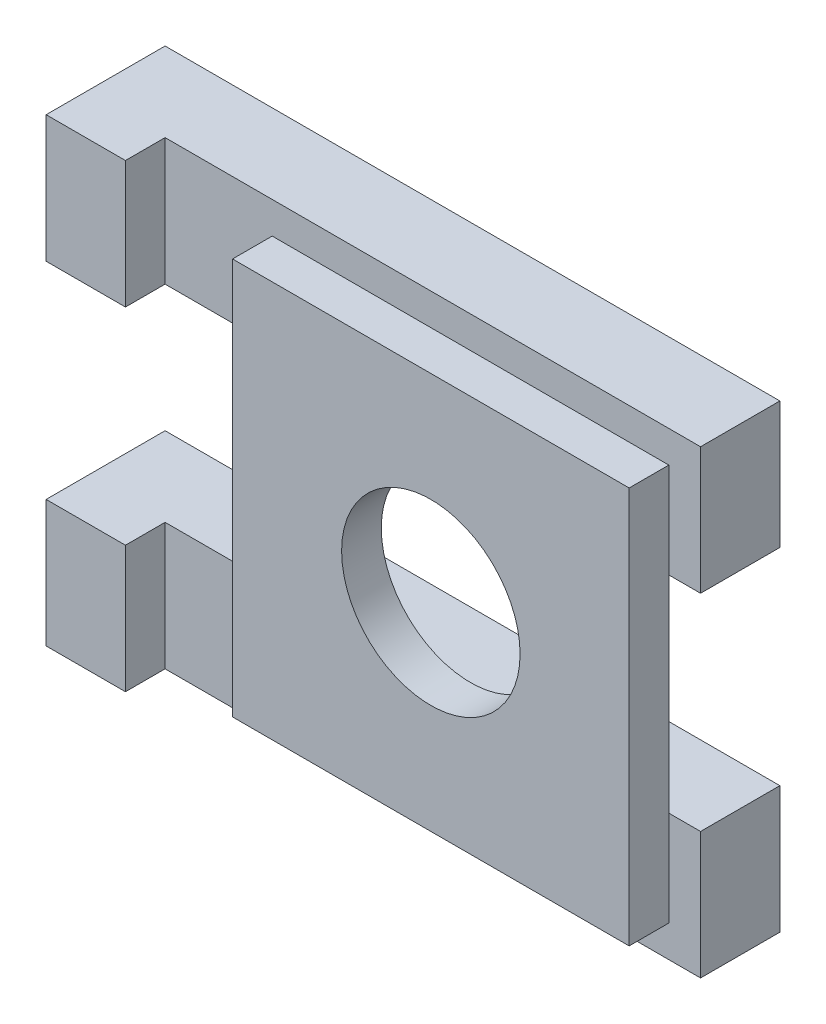
SolidWorks part; units mm, degrees
ref_plane "Płaszczyzna przednia" through (0, 0, 0) normal (0, 0, 1) x (1, 0, 0)
ref_plane "Płaszczyzna górna" through (0, 0, 0) normal (0, 1, 0) x (1, 0, 0)
ref_plane "Płaszczyzna prawa" through (0, 0, 0) normal (1, 0, 0) x (0, 0, -1)
sketch "Szkic1" plane through (0, 0, 0) normal (0, 0, 1) x (1, 0, 0)
  line L1 (-50, 50) -> (50, 50)
  line L2 (-50, 50) -> (-50, -50)
  line L3 (-50, -50) -> (50, -50)
  line L4 (50, 50) -> (50, -50)
  line L5 (-50, 50) -> (50, -50) construction
  line L6 (-50, -50) -> (50, 50) construction
  circle A0 centre (0, 0) radius 22.5
  point P0 (0, 0)
  dimension "D3" = 45
  dimension "D1" = 100
  dimension "D2" = 100
extrude "Dodanie-wyciągnięcie1" add sketch "Szkic1" along normal blind 10
sketch "Szkic2" plane through (0, 0, 0) normal (0, 0, -1) x (-1, 0, 0)
  line L0 (-50, -50) -> (-50, 50) construction
  line L1 (-58, 58) -> (97, 58)
  line L2 (-58, 58) -> (-58, 26)
  line L3 (-58, 26) -> (97, 26)
  line L4 (97, 58) -> (97, 26)
  line L5 (-50, 50) -> (50, 50) construction
  line L6 (0, 0) -> (75.488, 0) construction
  line L7 (-58, -26) -> (97, -26)
  line L8 (97, -58) -> (97, -26)
  line L9 (-58, -58) -> (97, -58)
  line L10 (-58, -58) -> (-58, -26)
  dimension "D1" = 8
  dimension "D2" = 8
  dimension "D3" = 32
  dimension "D4" = 155
extrude "Dodanie-wyciągnięcie2" add sketch "Szkic2" along normal blind 20
sketch "Szkic3" plane through (0, 0, 0) normal (0, 0, 1) x (1, 0, 0)
  line L1 (-97, 58) -> (-77, 58)
  line L2 (-97, 58) -> (-97, 26)
  line L3 (-97, 26) -> (-77, 26)
  line L4 (-77, 58) -> (-77, 26)
  line L5 (-97, -26) -> (-77, -26)
  line L6 (-97, -26) -> (-97, -58)
  line L7 (-97, -58) -> (-77, -58)
  line L8 (-77, -26) -> (-77, -58)
  point P4 (0, 0)
  point P10 (0, 0)
  dimension "D1" = 32
  dimension "D2" = 20
  dimension "D3" = 32
  dimension "D4" = 20
extrude "Dodanie-wyciągnięcie3" add sketch "Szkic3" along normal blind 10
